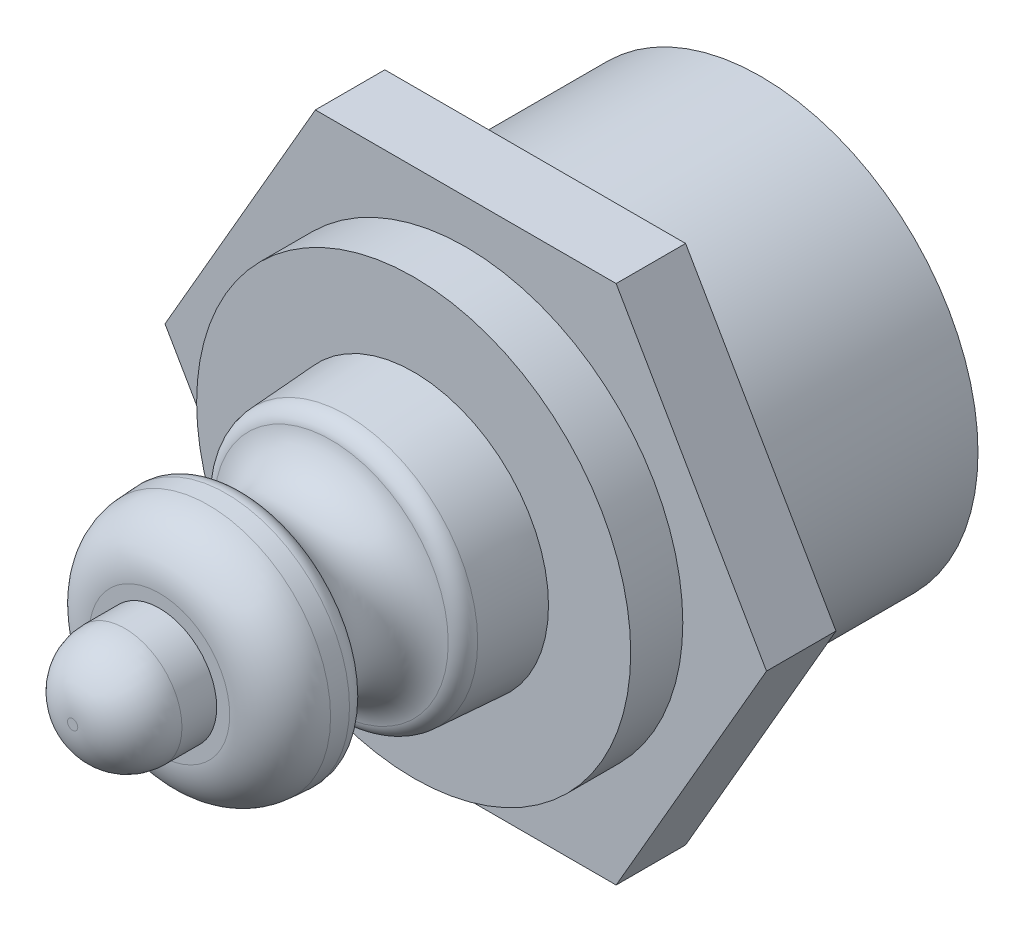
SolidWorks part; units mm, degrees
ref_plane "Front Plane" through (0, 0, 0) normal (0, 0, 1) x (1, 0, 0)
ref_plane "Top Plane" through (0, 0, 0) normal (0, 1, 0) x (1, 0, 0)
ref_plane "Right Plane" through (0, 0, 0) normal (1, 0, 0) x (0, 0, -1)
sketch "Sketch1" plane through (0, 0, 0) normal (0, 0, 1) x (1, 0, 0)
  circle A0 centre (0, 0) radius 7.9375
  dimension "D1" = 15.875
extrude "Extrude1" add sketch "Sketch1" along normal blind 12.7
ref_plane "Plane1" through (0, 0, 10.795) normal (0, 0, 1) x (1, 0, 0)
sketch "Sketch2" plane through (0, 0, 10.795) normal (0, 0, 1) x (1, 0, 0)
  line L0 (6.985, 0) -> (-6.985, 0) construction
  line L1 (5.4993, 9.525) -> (-5.4993, 9.525)
  line L2 (-5.4993, 9.525) -> (-10.9985, 0)
  line L3 (-10.9985, 0) -> (-5.4993, -9.525)
  line L4 (-5.4993, -9.525) -> (5.4993, -9.525)
  line L5 (5.4993, -9.525) -> (10.9985, 0)
  line L6 (10.9985, 0) -> (5.4993, 9.525)
  circle A0 centre (0, 0) radius 9.525 construction
  dimension "D1" = 19.05
extrude "Extrude2" add sketch "Sketch2" against normal blind 2.54
sketch "Sketch4" plane through (0, 0, 0) normal (0, 1, 0) x (1, 0, 0)
  line L0 (-4.9311, -12.7) -> (-4.748, -15.6842)
  line L1 (-7.9375, -12.7) -> (7.9375, -12.7) construction
  line L2 (-4.3608, -21.9962) -> (0, -21.9962)
  line L3 (0, -12.7) -> (0, -25.4497) construction
  line L4 (-4.5438, -19.012) -> (-4.3608, -21.9962)
  line L5 (-4.9311, -12.7) -> (0, -12.7)
  line L6 (0, -21.9962) -> (0, -12.7)
  arc A0 (-4.5438, -19.012) -> (-4.748, -15.6842) centre (-4.6459, -17.3481) ccw
revolve "Revolve1" add sketch "Sketch4" angle 360 about L3
fillet "Fillet1" radius 1.905 1 edges at (-4.3608, 0, 21.9962)
sketch "Sketch5" plane through (0, 0, 21.9962) normal (0, 0, 1) x (1, 0, 0)
  circle A0 centre (0, 0) radius 2.0924
extrude "Extrude3" add sketch "Sketch5" along normal blind 3.175
fillet "Fillet2" radius 1.905 1 edges at (2.0924, 0, 25.1712)
fillet "Fillet3" radius 0.635 2 edges at (-4.748, 0, 15.6842) (-4.5438, 0, 19.012)
